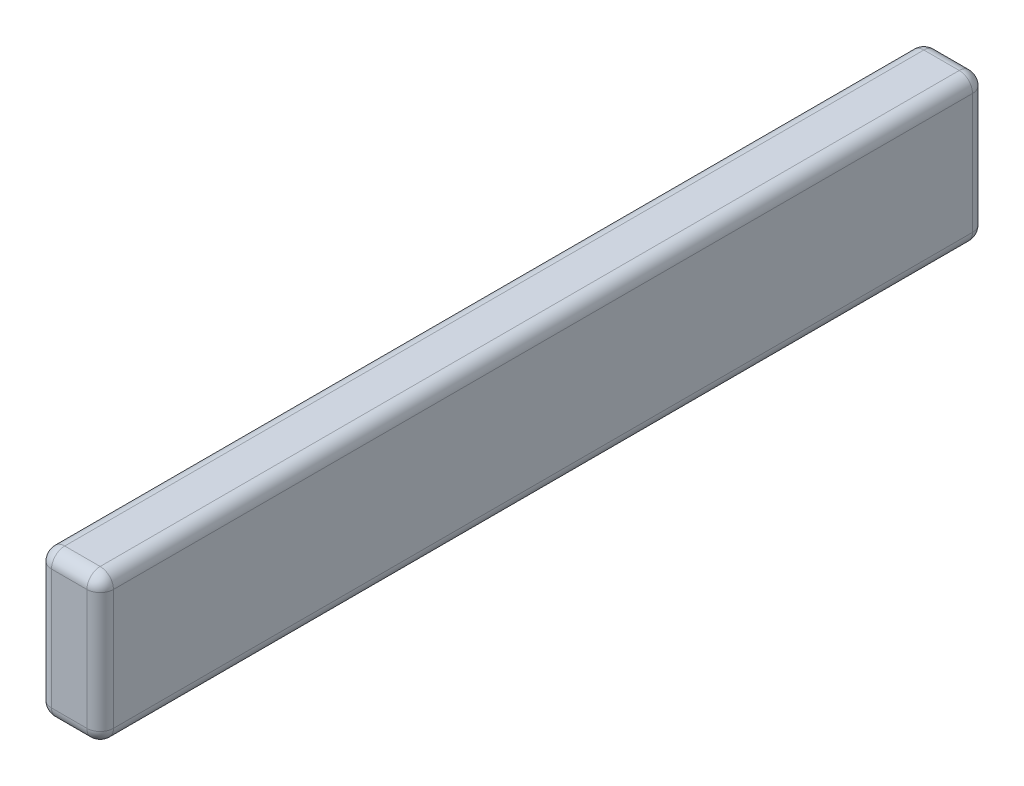
SolidWorks part; units mm, degrees
ref_plane "Front Plane" through (0, 0, 0) normal (0, 0, 1) x (1, 0, 0)
ref_plane "Top Plane" through (0, 0, 0) normal (0, 1, 0) x (1, 0, 0)
ref_plane "Right Plane" through (0, 0, 0) normal (1, 0, 0) x (0, 0, -1)
sketch "Sketch1" plane through (0, 0, 0) normal (1, 0, 0) x (0, 0, -1)
  line L1 (1000, 165.8) -> (-1000, 165.8)
  line L2 (1000, 165.8) -> (1000, -165.8)
  line L3 (1000, -165.8) -> (-1000, -165.8)
  line L4 (-1000, 165.8) -> (-1000, -165.8)
  line L5 (1000, 165.8) -> (-1000, -165.8) construction
  line L6 (1000, -165.8) -> (-1000, 165.8) construction
  point P0 (0, 0)
  dimension "D1" = 2000
  dimension "D2" = 331.6
extrude "Boss-Extrude1" add sketch "Sketch1" along normal blind 140
fillet "Fillet1" radius 30 12 edges at (70, -165.8, 1000) (70, -165.8, -1000) (70, 165.8, -1000) (70, 165.8, 1000) (0, -165.8, 0) (0, 0, -1000) (0, 165.8, 0) (0, 0, 1000) (140, 165.8, 0) (140, 0, -1000) (140, -165.8, 0) (140, 0, 1000)
